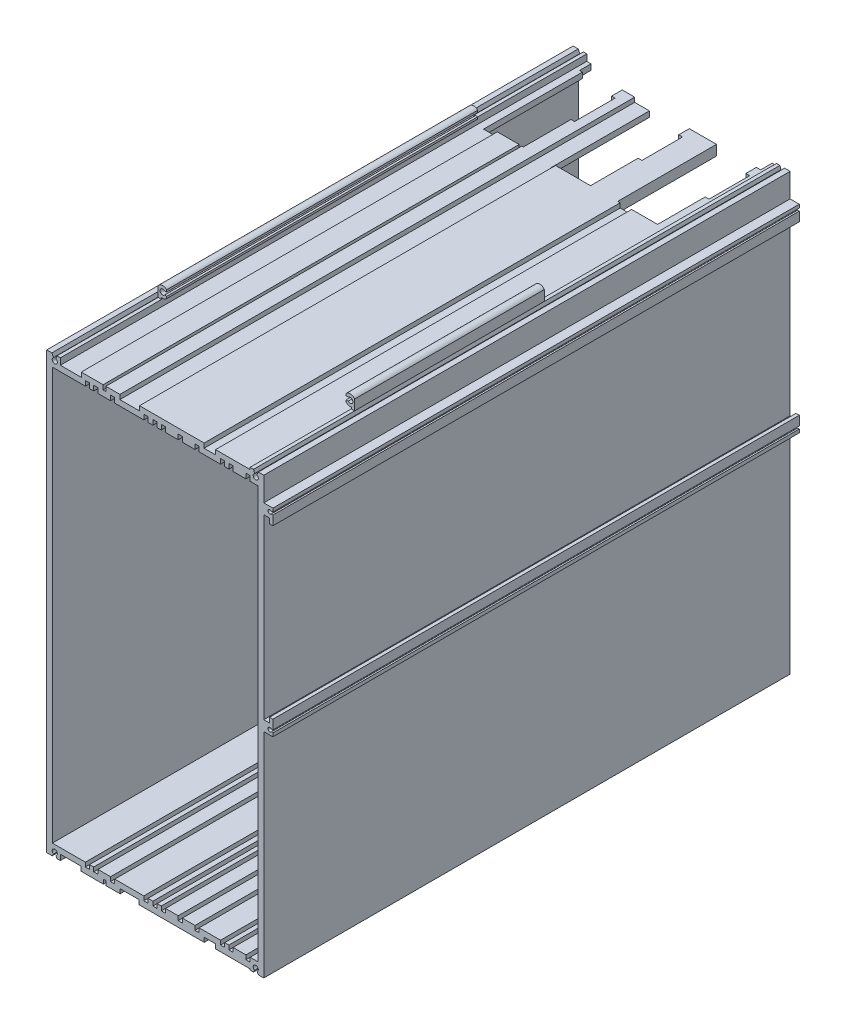
SolidWorks part; units mm, degrees
ref_plane "Front Plane" through (0, 0, 0) normal (0, 0, 1) x (1, 0, 0)
ref_plane "Top Plane" through (0, 0, 0) normal (0, 1, 0) x (1, 0, 0)
ref_plane "Right Plane" through (0, 0, 0) normal (1, 0, 0) x (0, 0, -1)
sketch "Sketch2" plane through (0, 0, 0) normal (0, 0, 1) x (1, 0, 0)
  line L0 (23.2732, 131.1707) -> (119.1108, 131.6725) construction
  line L1 (14.5, 261.3734) -> (14.5, 257.5858)
  line L2 (14.5, 257.5858) -> (26.7, 257.5858)
  line L3 (26.7, 257.5858) -> (26.7, 260.24)
  line L4 (26.7, 260.24) -> (39.5, 260.24)
  line L5 (39.5, 260.24) -> (39.5, 257.5858)
  line L6 (39.5, 257.5858) -> (41.1, 257.5858)
  line L7 (41.1, 257.5858) -> (41.1, 260.24)
  line L8 (41.1, 260.24) -> (49.3, 260.24)
  line L9 (49.3, 260.24) -> (49.3, 257.5858)
  line L10 (49.3, 257.5858) -> (60.8, 257.5858)
  line L11 (60.8, 257.5858) -> (60.8, 260.24)
  line L12 (60.8, 260.24) -> (98.6, 260.24)
  line L13 (98.6, 260.24) -> (98.6, 257.5858)
  line L14 (98.6, 257.5858) -> (105.3, 257.5858)
  line L15 (105.3, 257.5858) -> (105.3, 260.24)
  line L16 (105.3, 260.24) -> (125.5, 260.24)
  line L17 (125.5, 260.24) -> (125.5, 261.3734)
  line L18 (125.5, 261.3734) -> (127.5, 261.3734)
  line L19 (133.5, 261.3734) -> (133.5, 247.3734)
  line L20 (133.5, 247.3734) -> (138.85, 247.3734)
  line L21 (138.85, 247.3734) -> (138.85, 238.4234)
  line L22 (138.85, 238.4234) -> (136.9, 238.4234)
  line L23 (136.9, 238.4234) -> (136.9, 241.3734)
  line L24 (136.9, 241.3734) -> (133.5, 241.3734)
  line L25 (133.5, 241.3734) -> (133.5, 137.4734)
  line L26 (133.5, 137.4734) -> (136.9, 137.4734)
  line L27 (136.9, 137.4734) -> (136.9, 140.4234)
  line L28 (136.9, 140.4234) -> (138.85, 140.4234)
  line L29 (138.85, 140.4234) -> (138.85, 131.4734)
  line L30 (138.85, 131.4734) -> (133.5, 131.4734)
  line L31 (133.5, 131.4734) -> (133.5, 6.5734)
  line L32 (133.5, 6.5734) -> (130.3, 6.5734)
  line L33 (125.5, 6.5734) -> (125.5, 7.202)
  line L34 (125.5, 7.202) -> (105.25, 7.202)
  line L35 (105.25, 7.202) -> (105.25, 9.7858)
  line L36 (105.25, 9.7858) -> (98.65, 9.7858)
  line L37 (98.65, 9.7858) -> (98.65, 7.202)
  line L38 (98.65, 7.202) -> (60.55, 7.202)
  line L39 (60.55, 7.202) -> (60.55, 9.7858)
  line L40 (60.55, 9.7858) -> (49.45, 9.7858)
  line L41 (49.45, 9.7858) -> (49.45, 7.202)
  line L42 (49.45, 7.202) -> (41.2, 7.202)
  line L43 (41.2, 7.202) -> (41.2, 9.7858)
  line L44 (41.2, 9.7858) -> (39.6964, 9.7858)
  line L45 (39.6964, 9.7858) -> (39.6964, 7.202)
  line L46 (39.6964, 7.202) -> (26.5964, 7.202)
  line L47 (26.5964, 7.202) -> (26.5964, 9.7858)
  line L48 (26.5964, 9.7858) -> (14.4964, 9.7858)
  line L49 (14.4964, 9.7858) -> (14.4964, 6.5734)
  line L50 (14.4964, 6.5734) -> (12.4964, 6.5734)
  line L51 (6.5, 6.5734) -> (6.5, 261.3734)
  line L52 (6.5, 261.3734) -> (9.5, 261.3734)
  line L53 (9.8, 254.2858) -> (29.1, 254.2858)
  line L54 (29.1, 254.2858) -> (29.1, 257.1858)
  line L55 (29.1, 257.1858) -> (31.55, 257.1858)
  line L56 (31.55, 257.1858) -> (31.55, 254.2858)
  line L57 (31.55, 254.2858) -> (34, 254.2858)
  line L58 (34, 254.2858) -> (34, 257.1858)
  line L59 (34, 257.1858) -> (36.45, 257.1858)
  line L60 (36.45, 257.1858) -> (36.45, 254.2858)
  line L61 (36.45, 254.2858) -> (43.85, 254.2858)
  line L62 (43.85, 254.2858) -> (43.85, 257.1858)
  line L63 (43.85, 257.1858) -> (46.3, 257.1858)
  line L64 (46.3, 257.1858) -> (46.3, 254.2858)
  line L65 (46.3, 254.2858) -> (63.3, 254.2858)
  line L66 (63.3, 254.2858) -> (63.3, 257.1858)
  line L67 (63.3, 257.1858) -> (65.75, 257.1858)
  line L68 (65.75, 257.1858) -> (65.75, 254.2858)
  line L69 (65.75, 254.2858) -> (68.65, 254.2858)
  line L70 (68.65, 254.2858) -> (68.65, 257.1858)
  line L71 (68.65, 257.1858) -> (71.1, 257.1858)
  line L72 (71.1, 257.1858) -> (71.1, 254.2858)
  line L73 (71.1, 254.2858) -> (73.55, 254.2858)
  line L74 (73.55, 254.2858) -> (73.55, 257.1858)
  line L75 (73.55, 257.1858) -> (76, 257.1858)
  line L76 (76, 257.1858) -> (76, 254.2858)
  line L77 (76, 254.2858) -> (83.4, 254.2858)
  line L78 (83.4, 254.2858) -> (83.4, 257.1858)
  line L79 (83.4, 257.1858) -> (85.85, 257.1858)
  line L80 (85.85, 257.1858) -> (85.85, 254.2858)
  line L81 (85.85, 254.2858) -> (93.25, 254.2858)
  line L82 (93.25, 254.2858) -> (93.25, 257.1858)
  line L83 (93.25, 257.1858) -> (95.7, 257.1858)
  line L84 (95.7, 257.1858) -> (95.7, 254.2858)
  line L85 (95.7, 254.2858) -> (108.2, 254.2858)
  line L86 (108.2, 254.2858) -> (108.2, 257.1858)
  line L87 (108.2, 257.1858) -> (110.65, 257.1858)
  line L88 (110.65, 257.1858) -> (110.65, 254.2858)
  line L89 (110.65, 254.2858) -> (113.1, 254.2858)
  line L90 (113.1, 254.2858) -> (113.1, 257.1858)
  line L91 (113.1, 257.1858) -> (115.55, 257.1858)
  line L92 (115.55, 257.1858) -> (115.55, 254.2858)
  line L93 (115.55, 254.2858) -> (123.05, 254.2858)
  line L94 (123.05, 254.2858) -> (123.05, 257.1858)
  line L95 (123.05, 257.1858) -> (125.5, 257.1858)
  line L96 (125.5, 257.1858) -> (125.5, 254.2858)
  line L97 (125.5, 254.2858) -> (130.2, 254.2858)
  line L98 (130.2, 254.2858) -> (130.2, 13.0858)
  line L99 (130.2, 13.0858) -> (125.5, 13.0858)
  line L100 (125.5, 13.0858) -> (125.5, 10.6056)
  line L101 (125.5, 10.6056) -> (123.05, 10.6056)
  line L102 (123.05, 10.6056) -> (123.05, 13.0858)
  line L103 (123.05, 13.0858) -> (115.55, 13.0858)
  line L104 (115.55, 13.0858) -> (115.55, 10.6056)
  line L105 (115.55, 10.6056) -> (113.1, 10.6056)
  line L106 (113.1, 10.6056) -> (113.1, 13.0858)
  line L107 (113.1, 13.0858) -> (110.65, 13.0858)
  line L108 (110.65, 13.0858) -> (110.65, 10.6056)
  line L109 (110.65, 10.6056) -> (108.2, 10.6056)
  line L110 (108.2, 10.6056) -> (108.2, 13.0858)
  line L111 (108.2, 13.0858) -> (95.7, 13.0858)
  line L112 (95.7, 13.0858) -> (95.7, 10.6056)
  line L113 (95.7, 10.6056) -> (93.25, 10.6056)
  line L114 (93.25, 10.6056) -> (93.25, 13.0858)
  line L115 (93.25, 13.0858) -> (85.85, 13.0858)
  line L116 (85.85, 13.0858) -> (85.85, 10.6056)
  line L117 (85.85, 10.6056) -> (83.4, 10.6056)
  line L118 (83.4, 10.6056) -> (83.4, 13.0858)
  line L119 (83.4, 13.0858) -> (76, 13.0858)
  line L120 (76, 13.0858) -> (76, 10.6056)
  line L121 (76, 10.6056) -> (73.55, 10.6056)
  line L122 (73.55, 10.6056) -> (73.55, 13.0858)
  line L123 (73.55, 13.0858) -> (71.1, 13.0858)
  line L124 (71.1, 13.0858) -> (71.1, 10.6056)
  line L125 (71.1, 10.6056) -> (68.65, 10.6056)
  line L126 (68.65, 10.6056) -> (68.65, 13.0858)
  line L127 (68.65, 13.0858) -> (65.75, 13.0858)
  line L128 (65.75, 13.0858) -> (65.75, 10.6056)
  line L129 (65.75, 10.6056) -> (63.3, 10.6056)
  line L130 (63.3, 10.6056) -> (63.3, 13.0858)
  line L131 (63.3, 13.0858) -> (46.3, 13.0858)
  line L132 (46.3, 13.0858) -> (46.3, 10.6056)
  line L133 (46.3, 10.6056) -> (43.85, 10.6056)
  line L134 (43.85, 10.6056) -> (43.85, 13.0858)
  line L135 (43.85, 13.0858) -> (36.45, 13.0858)
  line L136 (36.45, 13.0858) -> (36.45, 10.6056)
  line L137 (36.45, 10.6056) -> (34, 10.6056)
  line L138 (34, 10.6056) -> (34, 13.0858)
  line L139 (34, 13.0858) -> (31.55, 13.0858)
  line L140 (31.55, 13.0858) -> (31.55, 10.6056)
  line L141 (31.55, 10.6056) -> (29.1, 10.6056)
  line L142 (29.1, 10.6056) -> (29.1, 13.0858)
  line L143 (29.1, 13.0858) -> (9.8, 13.0858)
  line L144 (9.8, 13.0858) -> (9.8, 254.2858)
  line L145 (11.2, 258.1858) -> (12.5, 261.3734)
  line L146 (11.2, 258.1858) -> (9.5, 261.3734)
  line L147 (12.5, 261.3734) -> (14.5, 261.3734)
  line L148 (128.8, 258.1858) -> (127.5, 261.3734)
  line L149 (128.8, 258.1858) -> (130.3, 261.3734)
  line L150 (130.3, 261.3734) -> (133.5, 261.3734)
  line L151 (138.85, 245.3734) -> (137.9352, 245.3734)
  line L152 (138.85, 243.8734) -> (137.8905, 243.8734)
  line L153 (138.85, 133.4734) -> (137.9352, 133.4734)
  line L154 (138.85, 134.9734) -> (137.8905, 134.9734)
  line L155 (128.8, 9.1858) -> (130.3, 6.5734)
  line L156 (128.8, 9.1858) -> (127.5, 6.5734)
  line L157 (127.5, 6.5734) -> (125.5, 6.5734)
  line L158 (11.2, 9.1858) -> (12.4964, 6.5734)
  line L159 (11.2, 9.1858) -> (9.7, 6.5734)
  line L160 (9.7, 6.5734) -> (6.5, 6.5734)
  circle A1 centre (11.2, 258.1858) radius 1.5
  circle A2 centre (128.8, 258.1858) radius 1.5
  circle A3 centre (137.075, 244.6484) radius 1.125
  circle A4 centre (137.075, 134.1984) radius 1.125
  circle A5 centre (128.8, 9.1858) radius 1.5
  circle A6 centre (11.2, 9.1858) radius 1.5
  point P51 (54.8, 13.0858)
  dimension "D1" = 127
  dimension "D87" = 3.2
  dimension "D90" = 3
  dimension "D92" = 2.4
  dimension "D93" = 3
  dimension "D97" = 5.75
  dimension "D101" = 5.75
  dimension "D106" = 3
  dimension "D111" = 3
  dimension "D2" = 3.3
  dimension "D3" = 3.3
  dimension "D4" = 120.4
  dimension "D5" = 8
  dimension "D6" = 8
  dimension "D7" = 3.3
  dimension "D8" = 3.3
  dimension "D9" = 254.8
  dimension "D10" = 247.8
  dimension "D11" = 241.2
  dimension "D12" = 12.2
  dimension "D13" = 12.8
  dimension "D14" = 1.6
  dimension "D15" = 37.8
  dimension "D16" = 8.2
  dimension "D17" = 11.5
  dimension "D18" = 6.7
  dimension "D19" = 20.2
  dimension "D20" = 19.3
  dimension "D21" = 2.9
  dimension "D22" = 2.45
  dimension "D23" = 2.45
  dimension "D24" = 2.45
  dimension "D25" = 2.45
  dimension "D26" = 2.45
  dimension "D27" = 2.45
  dimension "D28" = 2.45
  dimension "D29" = 2.45
  dimension "D30" = 2.45
  dimension "D31" = 2.45
  dimension "D32" = 2.45
  dimension "D33" = 2.45
  dimension "D34" = 7.4
  dimension "D35" = 17
  dimension "D36" = 19.3
  dimension "D37" = 2.9
  dimension "D38" = 2.45
  dimension "D39" = 7.4
  dimension "D40" = 7.4
  dimension "D41" = 12.5
  dimension "D42" = 2.45
  dimension "D43" = 7.5
  dimension "D44" = 4.7
  dimension "D45" = 2.45
  dimension "D46" = 2.45
  dimension "D47" = 2.45
  dimension "D48" = 7.4
  dimension "D49" = 2.45
  dimension "D50" = 17
  dimension "D51" = 2.45
  dimension "D52" = 2.9
  dimension "D53" = 2.45
  dimension "D54" = 2.45
  dimension "D55" = 2.45
  dimension "D56" = 7.4
  dimension "D57" = 2.45
  dimension "D58" = 7.4
  dimension "D59" = 2.45
  dimension "D60" = 12.5
  dimension "D61" = 2.45
  dimension "D62" = 2.45
  dimension "D63" = 2.45
  dimension "D64" = 7.5
  dimension "D65" = 2.45
  dimension "D66" = 4.7
  dimension "D67" = 7.9964
  dimension "D68" = 12.1
  dimension "D69" = 13.1
  dimension "D70" = 8.25
  dimension "D71" = 11.1
  dimension "D72" = 38.1
  dimension "D73" = 6.6
  dimension "D74" = 20.25
  dimension "D75" = 8
  dimension "D76" = 14
  dimension "D77" = 6
  dimension "D78" = 8.95
  dimension "D79" = 3.4
  dimension "D80" = 1.95
  dimension "D81" = 6
  dimension "D82" = 8.95
  dimension "D83" = 3.4
  dimension "D84" = 1.95
  dimension "D85" = 5.35
  dimension "D86" = 103.9
  dimension "D88" = 2.4
  dimension "D89" = 3
  dimension "D91" = 2
  dimension "D94" = 3.2
  dimension "D95" = 2
  dimension "D96" = 3.2
  dimension "D98" = 1.6
  dimension "D99" = 2
  dimension "D100" = 5.45
  dimension "D102" = 1.6
  dimension "D103" = 2
  dimension "D104" = 5.45
  dimension "D105" = 1.5
  dimension "D107" = 2.4
  dimension "D108" = 3.2
  dimension "D109" = 2
  dimension "D110" = 3.2
  dimension "D112" = 2.4
  dimension "D113" = 3.2
  dimension "D114" = 3.2
  dimension "D115" = 2
extrude "Boss-Extrude1" add sketch "Sketch2" along normal blind 308 contours A6 L158 L50 L49 L48 L47 L46 L45 L44 L43 L42 L41 L40 L39 L38 L37 L36 L35 L34 L33 L157 L156 A5 L155 L32 L31 L30 L29 L153 A4 L154 L28 L27 L26 L25 L24 L23 L22 L21 L152 A3 L151 L20 L19 L150 L149 A2 L148 L18
ref_plane "Plane1" through (0, 0, 60) normal (0, 0, -1) x (-1, 0, 0)
sketch "Sketch3" plane through (0, 0, 60) normal (0, 0, -1) x (-1, 0, 0)
  line L0 (-127.5, 261.3734) -> (-127.5, 267.3734)
  line L1 (-122.5, 270.1784) -> (-122.5, 262.1784)
  line L2 (-125.5, 261.3734) -> (-125.5, 269.0865)
  line L3 (-121.7757, 266.54) -> (-123.9222, 266.54)
  line L4 (-121.7757, 264.44) -> (-123.7503, 264.44)
  line L5 (-133.5, 251.3903) -> (-6.5, 251.3903) construction
  line L6 (-133.5, 261.3734) -> (-133.5, 247.3734) construction
  line L7 (-6.5, 6.5734) -> (-6.5, 261.3734) construction
  line L8 (-105.3, 260.24) -> (-125.5, 260.24) construction
  line L10 (-70, 251.3903) -> (-70, 270.1784) construction
  line L11 (-14.5, 261.3734) -> (-14.5, 269.0865)
  line L12 (-12.5, 261.3734) -> (-12.5, 267.3734)
  line L13 (-18.2243, 264.44) -> (-16.2497, 264.44)
  line L14 (-18.2243, 266.54) -> (-16.0778, 266.54)
  line L15 (-17.5, 270.1784) -> (-17.5, 262.1784)
  line L16 (-127.5, 261.3734) -> (-125.5, 261.3734)
  line L17 (-14.5, 261.3734) -> (-12.5, 261.3734)
  circle A0 centre (-124.8514, 265.49) radius 3.25
  circle A2 centre (-124.9004, 265.4028) radius 1.5
  circle A6 centre (-15.0996, 265.4028) radius 1.5
  circle A7 centre (-15.1486, 265.49) radius 3.25
  dimension "D1" = 6.5
  dimension "D5" = 3
  dimension "D6" = 1.85
  dimension "D2" = 5
  dimension "D3" = 6
  dimension "D4" = 2
  dimension "D7" = 2.2
  dimension "D8" = 2.2
extrude "Boss-Extrude2" add sketch "Sketch3" against normal blind 188.8 contours A7 L11 A6 L13 L15 | A7 L12 L11 A6 | L12 A7 L11 L17 | A7 L15 L14 A6 L11 | A0 L0 L16 L2 | A2 L2 A0 L0 | A2 L3 L1 A0 L2 | A2 L2 A0 L1 L4
sketch "Sketch4" plane through (127.5, 0, 0) normal (1, 0, 0) x (0, 0, -1)
  line L0 (-248.8, 261.3734) -> (-248.8, 267.3734) construction
  line L5 (-60, 261.3734) -> (-137.8, 261.3734)
  line L6 (-60, 261.3734) -> (-60, 282.1971)
  line L7 (-60, 282.1971) -> (-137.8, 282.1971)
  line L8 (-137.8, 261.3734) -> (-137.8, 282.1971)
  line L9 (-60, 261.3734) -> (-137.8, 282.1971) construction
  line L10 (-60, 282.1971) -> (-137.8, 261.3734) construction
  point P4 (-98.9, 271.7852)
  dimension "D1" = 111
extrude "Cut-Extrude3" cut sketch "Sketch4" against normal up to next
sketch "Sketch5" plane through (0, 260.24, 0) normal (0, 1, 0) x (1, 0, 0)
  line L0 (105.3, 0) -> (125.5, 0) construction
  line L1 (17, -6.75) -> (123, -6.75)
  line L2 (17, -6.75) -> (17, 0)
  line L3 (17, 0) -> (123, 0)
  line L4 (123, -6.75) -> (123, 0)
  line L5 (17, -6.75) -> (123, 0) construction
  line L6 (17, 0) -> (123, -6.75) construction
  line L7 (14.5, -60) -> (14.5, 0) construction
  line L8 (125.5, -137.8) -> (125.5, 0) construction
  point P4 (70, -3.375)
  dimension "D1" = 106
  dimension "D2" = 2.5
  dimension "D3" = 6.75
  dimension "D4" = 2.5
extrude "Cut-Extrude4" cut sketch "Sketch5" against normal up to next
sketch "Sketch6" plane through (0, 260.24, 0) normal (0, 1, 0) x (1, 0, 0)
  line L0 (105.3, -6.75) -> (123, -6.75) construction
  line L1 (120.5, -6.75) -> (97.15, -6.75)
  line L2 (120.5, -6.75) -> (120.5, -64.55)
  line L3 (120.5, -64.55) -> (97.15, -64.55)
  line L4 (97.15, -6.75) -> (97.15, -64.55)
  line L5 (120.5, -6.75) -> (97.15, -64.55) construction
  line L6 (120.5, -64.55) -> (97.15, -6.75) construction
  line L7 (125.5, -308) -> (125.5, 0) construction
  line L8 (133.5, 0) -> (138.85, 0) construction
  line L9 (60.8, -6.75) -> (98.6, -6.75) construction
  line L10 (81.25, -6.75) -> (57.9, -6.75)
  line L11 (81.25, -6.75) -> (81.25, -64.55)
  line L12 (81.25, -64.55) -> (57.9, -64.55)
  line L13 (57.9, -6.75) -> (57.9, -64.55)
  line L14 (81.25, -6.75) -> (57.9, -64.55) construction
  line L15 (81.25, -64.55) -> (57.9, -6.75) construction
  line L16 (60.8, -6.75) -> (49.3, -6.75) construction
  line L17 (42, -6.75) -> (18.65, -6.75)
  line L18 (42, -6.75) -> (42, -64.55)
  line L19 (42, -64.55) -> (18.65, -64.55)
  line L20 (18.65, -6.75) -> (18.65, -64.55)
  line L21 (42, -6.75) -> (18.65, -64.55) construction
  line L22 (42, -64.55) -> (18.65, -6.75) construction
  point P4 (108.825, -35.65)
  point P15 (69.575, -35.65)
  point P22 (30.325, -35.65)
  dimension "D1" = 23.35
  dimension "D2" = 5
  dimension "D3" = 57.8
  dimension "D4" = 64.55
  dimension "D5" = 57.8
  dimension "D6" = 15.9
  dimension "D7" = 23.35
  dimension "D8" = 23.35
  dimension "D9" = 15.9
extrude "Cut-Extrude5" cut sketch "Sketch6" against normal up to next
sketch "Sketch7" plane through (12.5, 0, 0) normal (-1, 0, 0) x (0, 0, 1)
  line L1 (0, 261.3734) -> (66.8, 261.3734)
  line L2 (0, 261.3734) -> (0, 273.0065)
  line L3 (0, 273.0065) -> (66.8, 273.0065)
  line L4 (66.8, 261.3734) -> (66.8, 273.0065)
  line L5 (0, 261.3734) -> (66.8, 273.0065) construction
  line L6 (0, 273.0065) -> (66.8, 261.3734) construction
  point P4 (33.4, 267.19)
  dimension "D1" = 66.8
extrude "Cut-Extrude6" cut sketch "Sketch7" against normal up to next
sketch "Sketch8" plane through (0, 260.24, 0) normal (0, 1, 0) x (1, 0, 0)
  line L0 (120.5, -64.55) -> (120.5, -6.75) construction
  line L1 (120.5, -12.95) -> (122.75, -12.95)
  line L2 (120.5, -12.95) -> (120.5, -36.7)
  line L3 (120.5, -36.7) -> (122.75, -36.7)
  line L4 (122.75, -12.95) -> (122.75, -36.7)
  line L5 (120.5, -12.95) -> (122.75, -36.7) construction
  line L6 (120.5, -36.7) -> (122.75, -12.95) construction
  line L7 (120.5, -6.75) -> (123, -6.75) construction
  line L8 (81.25, -64.55) -> (81.25, -6.75) construction
  line L9 (81.25, -12.95) -> (83.5, -12.95)
  line L10 (81.25, -12.95) -> (81.25, -36.7)
  line L11 (81.25, -36.7) -> (83.5, -36.7)
  line L12 (83.5, -12.95) -> (83.5, -36.7)
  line L13 (81.25, -12.95) -> (83.5, -36.7) construction
  line L14 (81.25, -36.7) -> (83.5, -12.95) construction
  line L16 (41.8337, -12.95) -> (44.0837, -12.95)
  line L17 (41.8337, -12.95) -> (41.8337, -36.7)
  line L18 (41.8337, -36.7) -> (44.0837, -36.7)
  line L19 (44.0837, -12.95) -> (44.0837, -36.7)
  line L20 (41.8337, -12.95) -> (44.0837, -36.7) construction
  line L21 (41.8337, -36.7) -> (44.0837, -12.95) construction
  point P4 (121.625, -24.825)
  point P13 (82.375, -24.825)
  point P20 (42.9587, -24.825)
  dimension "D1" = 6.2
  dimension "D2" = 23.75
  dimension "D3" = 2.25
  dimension "D4" = 2.25
  dimension "D5" = 2.25
extrude "Cut-Extrude7" cut sketch "Sketch8" against normal up to next
